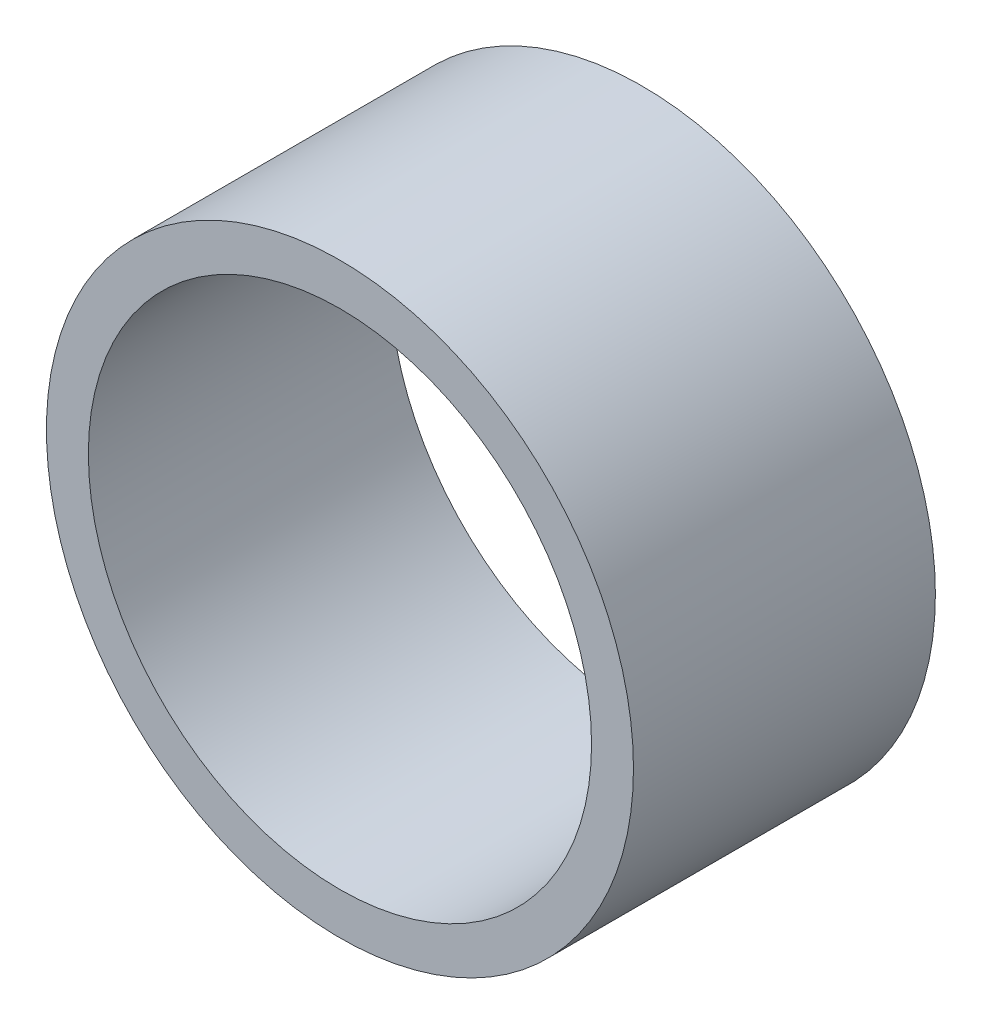
SolidWorks part; units mm, degrees
ref_plane "Front Plane" through (0, 0, 0) normal (0, 0, 1) x (1, 0, 0)
ref_plane "Top Plane" through (0, 0, 0) normal (0, 1, 0) x (1, 0, 0)
ref_plane "Right Plane" through (0, 0, 0) normal (1, 0, 0) x (0, 0, -1)
sketch "Sketch1" plane through (0, 0, 0) normal (0, 0, 1) x (1, 0, 0)
  circle A0 centre (0, 0) radius 45
  circle A1 centre (0, 0) radius 52.5
  dimension "D1" = 90
  dimension "D2" = 105
extrude "Boss-Extrude1" add sketch "Sketch1" along normal mid plane 54
